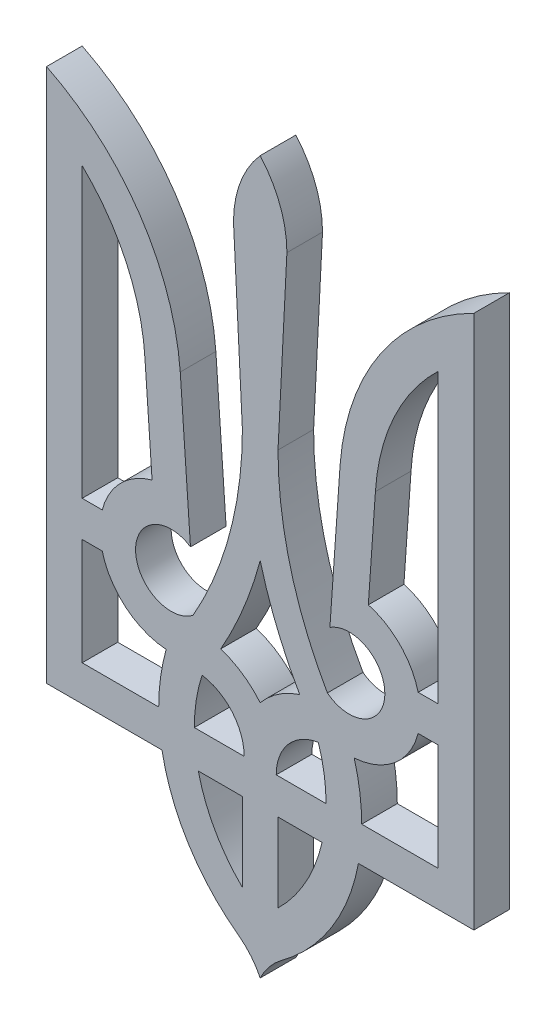
SolidWorks part; units mm, degrees
ref_plane "Спереди" through (0, 0, 0) normal (0, 0, 1) x (1, 0, 0)
ref_plane "Сверху" through (0, 0, 0) normal (0, 1, 0) x (1, 0, 0)
ref_plane "Справа" through (0, 0, 0) normal (1, 0, 0) x (0, 0, -1)
sketch "Эскиз1" plane through (0, 0, 0) normal (0, 0, 1) x (1, 0, 0)
  line L0 (0, 0) -> (-60, 0) construction
  line L1 (0, 0) -> (0, -45) construction
  line L2 (-27.5833, -45) -> (-60, -45)
  line L3 (-60, -45) -> (-60, 105)
  line L4 (-22.4495, 49.493) -> (-19.5761, 8.4012)
  line L5 (-22.38, 48.4989) -> (-20.3847, 19.9658) construction
  line L6 (0, 0) -> (15, 0) construction
  line L7 (0, -35) -> (26.5, -35) construction
  line L8 (0, -35) -> (-50, -35) construction
  line L9 (-28.5, -35) -> (-50, -35)
  line L10 (-50, -35) -> (-50, -5)
  line L11 (-50, 5) -> (-50, 85.9092)
  line L12 (-60, -45) -> (-90, -45) construction
  line L13 (-50, -35) -> (-50, 105) construction
  line L14 (-90, -45) -> (-90, 44.25) construction
  line L15 (0, 0) -> (0, 129.6666) construction
  line L16 (-60, 0) -> (-25, 0) construction
  line L17 (-44.3649, 5) -> (-50, 5)
  line L18 (-32.3556, 47.8014) -> (-30.3604, 19.2683)
  line L19 (-44.3649, -5) -> (-50, -5)
  line L20 (0, -45) -> (0, -95.3664) construction
  line L21 (-5, -67.1364) -> (-5, -45)
  line L22 (0, -45) -> (-60, -45) construction
  line L23 (-5, -45) -> (-17.3748, -45)
  line L24 (-18.5, -35) -> (-4.5, -35)
  line L25 (0, -45) -> (60, -45) construction
  line L26 (60, -45) -> (60, 93.5) construction
  line L27 (60, 93.5) -> (22.5, 93.5) construction
  line L28 (-90, 44.25) -> (-110, 44.25) construction
  line L29 (-7.5, 93.5) -> (0, 93.5) construction
  line L30 (-5, 44.25) -> (-7.5, 93.5)
  line L31 (0, -95.3664) -> (-18.004, -95.3664) construction
  line L32 (0, 113.3431) -> (0, -86.6569)
  arc A0 (-22.4495, 49.493) -> (-60, 105) centre (-90, 44.25) ccw
  arc A1 (-50, 85.9092) -> (-32.3556, 47.8014) centre (-90, 44.25) cw
  arc A2 (-44.3649, -5) -> (-26.4011, -19.9509) centre (-25, 0) ccw
  arc A3 (-19.5761, 8.4012) -> (-18.8639, -7.8961) centre (-25, 0) ccw
  arc A4 (-26.4011, -19.9509) -> (-28.5, -35) centre (26.5, -35) ccw
  arc A5 (-18.5, -35) -> (-16.3222, -21.1704) centre (26.5, -35) cw
  arc A6 (-27.5833, -45) -> (-5.9458, -79.4103) centre (26.5, -35) ccw
  arc A7 (-30.3604, 19.2683) -> (-44.3649, 5) centre (-25, 0) ccw
  arc A8 (-17.3748, -45) -> (-5, -67.1364) centre (26.5, -35) ccw
  arc A9 (-4.5, -35) -> (-16.3222, -21.1704) centre (-18.5, -35) ccw
  arc A10 (0, 113.3431) -> (-7.5, 93.5) centre (22.5, 93.5) ccw
  arc A11 (-18.8639, -7.8961) -> (-5, 44.25) centre (-110, 44.25) ccw
  arc A12 (0, -86.6569) -> (-5.9458, -79.4103) centre (-18.004, -95.3664) ccw
  arc A14 (0, -19.7111) -> (-11.0914, -12.1721) centre (-18.5, -35) ccw
  arc A16 (-11.0914, -12.1721) -> (0, 14.8157) centre (-110, 44.25) ccw
  point P3 (0, 5)
  point P7 (-87.4973, 5)
  point P8 (260.5938, -135.0208)
  point P9 (-87.4973, -5)
  point P26 (-19.6695, 9.7374)
  point P27 (-32.4251, 48.7954)
  point P28 (-29.6451, 9.0398)
  dimension "D9" = 135.5074
  dimension "D10" = 10
  dimension "D11" = 35
  dimension "D12" = 40
  dimension "D13" = 20
  dimension "D19" = 26.5
  dimension "D20" = 113.87
  dimension "D22" = 10
  dimension "D23" = 45
  dimension "D24" = 45
  dimension "D25" = 28
  dimension "D29" = 60
  dimension "D31" = 210
  dimension "D34" = 18.004
  dimension "D35" = 48
  dimension "D33" = 200
  dimension "D21" = 40
  dimension "D1" = 120
  dimension "D2" = 45
  dimension "D3" = 5
  dimension "D4" = 150
  dimension "D5" = 5
  dimension "D7" = 30
  dimension "D8" = 89.25
  dimension "D14" = 4
  dimension "D15" = 60.7207
  dimension "D17" = 21.5
  dimension "D18" = 15
  dimension "D26" = 60
  dimension "D27" = 138.5
  dimension "D28" = 37.5
  dimension "D30" = 20
  dimension "D32" = 7.5
  dimension "D36" = 200
  dimension "D6" = 10
  dimension "D16" = 10
extrude "Бобышка-Вытянуть1" add sketch "Эскиз1" along normal blind 10 contours A14 A16 L32 A10 L30 A11 A3 L4 A0 L3 L2 A6 A12 L18 A7 L17 L11 A1 A2 A4 L9 L10 L19 A8 L23 L21 A9 L24 A5
mirror "Зеркальное отражение1" about plane through (0, 0, 0) normal (1, 0, 0) of "Бобышка-Вытянуть1"
scale "Масштаб1" scale about centroid uniform scaling yes scale factor 0.2
sketch "Эскиз2" plane through (0, 0, 0) normal (0, 0, 1) x (1, 0, 0)
  line L0 (0, 0) -> (0, 10) construction
  line L1 (-20, 40) -> (20, 40) construction
  line L2 (-20, 40) -> (-20, -20) construction
  line L3 (-20, -20) -> (20, -20) construction
  line L4 (20, 40) -> (20, -20) construction
  line L5 (-20, 40) -> (20, -20) construction
  line L6 (-20, -20) -> (20, 40) construction
  point P0 (0, 10)
  dimension "D1" = 40
  dimension "D2" = 60
